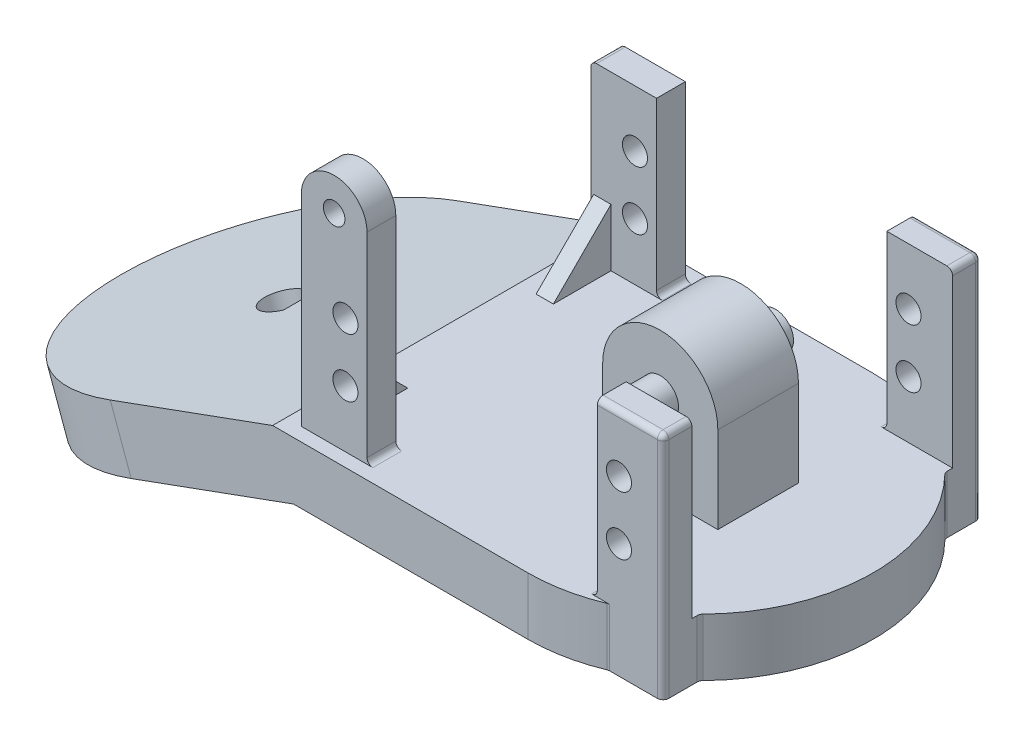
SolidWorks part; units mm, degrees
ref_plane "Plan de face" through (0, 0, 0) normal (0, 0, 1) x (1, 0, 0)
ref_plane "Plan de dessus" through (0, 0, 0) normal (0, 1, 0) x (1, 0, 0)
ref_plane "Plan de droite" through (0, 0, 0) normal (1, 0, 0) x (0, 0, -1)
sketch "Esquisse5" plane through (0, 0, 0) normal (0, 1, 0) x (1, 0, 0)
  line L0 (42.5, 0) -> (-42.5, 0) construction
  line L1 (42.5, -30) -> (-42.5, -30)
  line L2 (42.5, 30) -> (-42.5, 30)
  arc A0 (42.5, -30) -> (42.5, 30) centre (42.5, 0) ccw
  arc A1 (-42.5, 30) -> (-42.5, -30) centre (-42.5, 0) ccw
  point P2 (0, 0)
  dimension "D2" = 30
  dimension "D1" = 85
extrude "Boss.-Extru.3" add sketch "Esquisse5" along normal mid plane 10
sketch "Esquisse36" plane through (0, 0, 0) normal (0, 0, 1) x (1, 0, 0)
  line L0 (0, 0) -> (9.0993, -25)
  line L1 (9.0993, -25) -> (-112.5, -25)
  line L2 (-112.5, -25) -> (-112.5, 35)
  line L3 (-112.5, 35) -> (-12.739, 35)
  line L4 (-12.739, 35) -> (0, 0)
  line L5 (42.5, -5) -> (-42.5, -5) construction
  line L6 (42.5, 5) -> (-42.5, 5) construction
  line L7 (-42.5, 5) -> (-42.5, -5) construction
  dimension "D1" = 180
  dimension "D2" = 20
  dimension "D3" = 70
  dimension "D4" = 30
  dimension "D5" = 70
sketch "Esquisse7" plane through (0, 0, 0) normal (0, 0, 1) x (1, 0, 0)
  line L0 (42.5, 5) -> (32.5, 5)
  line L1 (-42.5, 5) -> (42.5, 5) construction
  line L2 (32.5, 5) -> (32.5, 20)
  line L3 (32.5, 20) -> (52.5, 20)
  line L4 (52.5, 20) -> (52.5, 5)
  line L5 (72.5, 5) -> (42.5, 5) construction
  line L6 (52.5, 5) -> (42.5, 5)
  arc A0 (32.5, 20) -> (52.5, 20) centre (42.5, 20) cw
  circle A1 centre (42.5, 20) radius 3.175
  dimension "D1" = 10
  dimension "D3" = 6.35
  dimension "D2" = 15
extrude "Boss.-Extru.5" add sketch "Esquisse7" along normal mid plane 14 contours A1 L3 A0 | A1 L3 L2 L0 L6 L4
sketch "Esquisse10" plane through (0, -5, 0) normal (0, -1, 0) x (1, 0, 0)
  point P0 (42.5, 0)
ref_plane "Plan1" through (0, 0, 22.64) normal (0, 0, 1) x (1, 0, 0)
sketch "Esquisse13" plane through (0, 0, 22.64) normal (0, 0, 1) x (1, 0, 0)
  line L0 (-42.5, 5) -> (42.5, 5) construction
  line L1 (5.8, 5) -> (58.63, 5)
  line L2 (5.8, 5) -> (5.8, 29.91) construction
  line L3 (5.8, 29.91) -> (58.63, 29.91) construction
  line L4 (58.63, 5) -> (58.63, 29.91) construction
  line L5 (5.8, 5) -> (0.8, 5)
  line L6 (0.8, 5) -> (0.8, 34.91)
  line L7 (0.8, 34.91) -> (63.63, 34.91)
  line L8 (63.63, 34.91) -> (63.63, 5)
  line L9 (63.63, 5) -> (58.63, 5)
  line L10 (63.63, 5) -> (58.63, 5)
  line L11 (0.8, 5) -> (5.8, 5)
  line L12 (12.215, 5) -> (12.215, 29.91)
  line L13 (12.215, 29.91) -> (52.215, 29.91)
  line L14 (52.215, 29.91) -> (52.215, 5)
  line L15 (52.215, 5) -> (12.215, 5)
  circle A0 centre (42.5, 20) radius 3.175 construction
  circle A2 centre (55.97, 25.08) radius 2.18
  circle A3 centre (55.97, 14.92) radius 2.18
  circle A4 centre (8.47, 25.08) radius 2.18
  circle A5 centre (8.47, 14.92) radius 2.18
  point P6 (58.63, 17.455)
  point P24 (32.215, 29.91)
  point P26 (32.215, 34.91)
  dimension "D4" = 5
  dimension "D7" = 4.36
  dimension "D8" = 47.5
  dimension "D12" = 10.16
  dimension "D1" = 52.83
  dimension "D2" = 16.13
  dimension "D3" = 24.91
  dimension "D5" = 4.83
  dimension "D6" = 2.67
  dimension "D9" = 47.5
  dimension "D10" = 0
  dimension "D11" = 0
  dimension "D13" = 0
  dimension "D14" = 5
  dimension "D15" = 5
  dimension "D16" = 40
  dimension "D17" = 0
  dimension "D18" = 0
extrude "Boss.-Extru.8" add sketch "Esquisse13" along normal blind 5 contours L13 L14 L1 L9 L8 L7 L6 L5 L12 A5 A4 A3 A2
sketch "Esquisse47" plane through (0, 0, 27.64) normal (0, 0, 1) x (1, 0, 0)
  line L0 (52.215, 29.91) -> (52.215, 5) construction
  line L1 (12.215, 29.91) -> (52.215, 29.91)
  line L2 (12.215, 29.91) -> (12.215, 34.91)
  line L3 (12.215, 34.91) -> (52.215, 34.91)
  line L4 (52.215, 29.91) -> (52.215, 34.91)
  line L5 (12.215, 29.91) -> (52.215, 34.91) construction
  line L6 (12.215, 34.91) -> (52.215, 29.91) construction
  line L7 (12.215, 5) -> (12.215, 29.91) construction
  line L8 (12.215, 29.91) -> (52.215, 29.91) construction
  line L9 (0.8, 34.91) -> (63.63, 34.91) construction
  point P4 (32.215, 32.41)
extrude "Enlèv. mat.-Extru.8" cut sketch "Esquisse47" against normal up to next
ref_plane "Plan12" through (2.8, 0, 0) normal (-1, 0, 0) x (0, 0, 1)
mirror "Symétrie2" about plane through (0, 0, 0) normal (0, 0, 1) of "Enlèv. mat.-Extru.8", "Boss.-Extru.8"
sketch "Esquisse14" plane through (0, 0, 0) normal (0, 0, 1) x (1, 0, 0)
  point P0 (42.5, 20)
sketch "Esquisse33" plane through (0, 5, 0) normal (0, -1, 0) x (1, 0, 0)
  line L0 (54.1632, -27.64) -> (63.63, -27.64) construction
  line L1 (63.63, 27.64) -> (54.1632, 27.64)
  line L2 (63.63, 27.64) -> (63.63, -27.64)
  line L3 (63.63, -27.64) -> (54.1632, -27.64)
  line L4 (54.1632, 27.64) -> (54.1632, -27.64)
  dimension "D1" = 0
  dimension "D2" = 0
extrude "Boss.-Extru.10" add sketch "Esquisse33" along normal up to surface (10 mm away) up to face at (0, -5, 0)
sketch "Esquisse34" plane through (0, 0, 0) normal (0, 1, 0) x (1, 0, 0)
  line L0 (0, 0) -> (0, 29.4868) construction
extrude "Enlèv. mat.-Extru.6" cut sketch "Esquisse36" against normal mid plane 130
ref_plane "Plan11" through (0, 0, 0) normal (-0.342, 0.9397, 0) x (0, 0, -1)
sketch "Esquisse35" plane through (0, 0, 0) normal (-0.342, 0.9397, 0) x (0, 0, -1)
  circle A0 centre (0, 30) radius 30
  dimension "D1" = 60
  dimension "D2" = 0
extrude "Boss.-Extru.11" add sketch "Esquisse35" along normal mid plane 10.64
sketch "Esquisse37" plane through (0, 0, 0) normal (0, 0, 1) x (1, 0, 0)
sketch "Esquisse38" plane through (-1.8195, 4.9992, 0) normal (-0.342, 0.9397, 0) x (0.9397, 0.342, 0)
  point P1 (-30, 0)
sketch "Esquisse39" plane through (1.8195, -4.9992, 0) normal (0.342, -0.9397, 0) x (0.9397, 0.342, 0)
  point P0 (-30, 0)
sketch "Esquisse40" plane through (0, 0, 0) normal (0, 0, 1) x (1, 0, 0)
  line L0 (-26.3712, -15.2598) -> (-30.0103, -5.2614)
  line L1 (-26.3712, -15.2598) -> (1.8195, -4.9992)
  line L2 (-30.0103, -5.2614) -> (-1.8195, 4.9992)
  line L3 (1.8195, -4.9992) -> (-1.8195, 4.9992)
  dimension "D1" = 0
extrude "Boss.-Extru.12" add sketch "Esquisse40" along normal mid plane 60
sketch "Esquisse41" plane through (-1.8195, 4.9992, 0) normal (-0.342, 0.9397, 0) x (0.9397, 0.342, 0)
  line L0 (-27.46, -2.2602) -> (-27.46, 2.2602)
  line L1 (0, -30) -> (0, 30) construction
  arc A1 (-27.46, -2.2602) -> (-27.46, 2.2602) centre (-30, 0) cw
  point P4 (-33.4, 0)
  dimension "D2" = 3.4
  dimension "D3" = 5.94
extrude "Enlèv. mat.-Extru.7" cut sketch "Esquisse41" against normal blind 60
sketch "Esquisse42" plane through (0, 0, 27.64) normal (0, 0, 1) x (1, 0, 0)
  line L0 (0.8, 34.91) -> (0.8, 39.91)
  line L1 (0.8, 39.91) -> (12.215, 39.91)
  line L2 (12.215, 39.91) -> (12.215, 34.91)
  line L3 (0.8, 34.91) -> (12.215, 34.91) construction
  line L4 (12.215, 34.91) -> (0.8, 34.91)
  line L5 (12.215, 5) -> (12.215, 34.91) construction
  arc A0 (0.8, 39.91) -> (12.215, 39.91) centre (6.5075, 39.91) cw
  circle A1 centre (6.5075, 39.91) radius 1.875
  line M15 (63.63, 34.91) -> (52.215, 34.91)
  dimension "D3" = 3.75
  dimension "D1" = 5
  dimension "D2" = 0
extrude "Boss.-Extru.13" add sketch "Esquisse42" against normal up to surface (5 mm away) contours A1 L1 A0 | A1 L1 L0 L2 M15
sketch "Esquisse45" plane through (2.8, 0, 0) normal (-1, 0, 0) x (0, 0, 1)
  line L0 (22.64, 14.9996) -> (12.64, 4.9996)
  line L1 (22.64, 5) -> (22.64, 39.91) construction
  line L2 (30, 4.9996) -> (-30, 4.9996) construction
  dimension "D1" = 10
  dimension "D2" = 10
rib "Nervure4" sketch "Esquisse45" sketch "Esquisse45" thickness 3 extrusion direction parallel to sketch draft on no parameters "D1"=3
fillet "Congé1" radius 1 6 edges at (54.1632, 0, 27.64) (63.63, 14.955, -27.64) (54.1632, 0, -27.64) (63.63, 14.955, 27.64) (63.63, 0, 21.2961) (63.63, 0, -21.2961)
mirror "Symétrie3" about plane through (0, 0, 0) normal (0, 0, 1) of "Nervure4"
fillet "Congé2" radius 1 11 edges at (63.3371, 34.91, -27.3471) (57.4225, 34.91, 27.64) (63.3371, 34.91, 27.3471) (63.63, 34.91, -24.64) (0.8, 34.91, -25.14) (52.215, 5, -25.14) (12.215, 5, -25.14) (12.215, 5, 25.14) (52.215, 5, 25.14) (63.63, 34.91, 24.64) (6.5075, 34.91, -27.64)
sketch "Esquisse48" plane through (0, 0, 0) normal (0, 0, 1) x (1, 0, 0)
  circle A0 centre (42.5, 20) radius 3.15
  point P2 (0, 0)
  dimension "D1" = 6.3
extrude "Boss.-Extru.14" add sketch "Esquisse48" along normal blind 13 and the other way blind 13
